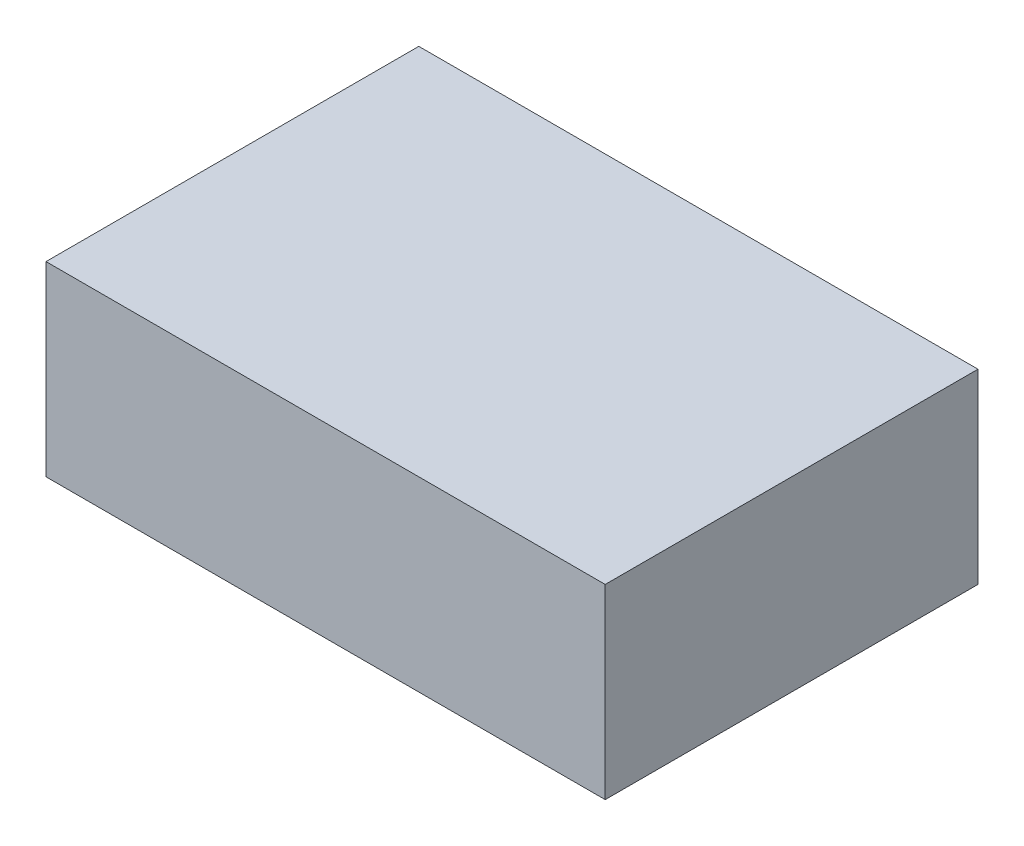
SolidWorks part; units mm, degrees
ref_plane "Front Plane" through (0, 0, 0) normal (0, 0, 1) x (1, 0, 0)
ref_plane "Top Plane" through (0, 0, 0) normal (0, 1, 0) x (1, 0, 0)
ref_plane "Right Plane" through (0, 0, 0) normal (1, 0, 0) x (0, 0, -1)
sketch "Sketch1" plane through (0, 0, 0) normal (0, 0, 1) x (1, 0, 0)
  line L1 (-15, -5) -> (15, -5)
  line L2 (-15, -5) -> (-15, 5)
  line L3 (-15, 5) -> (15, 5)
  line L4 (15, -5) -> (15, 5)
  line L5 (0, 5) -> (0, -5) construction
  line L6 (-15, 0) -> (15, 0) construction
  point P0 (0, 0)
  dimension "D1" = 10
  dimension "D2" = 30
extrude "Boss-Extrude1" add sketch "Sketch1" against normal blind 20
